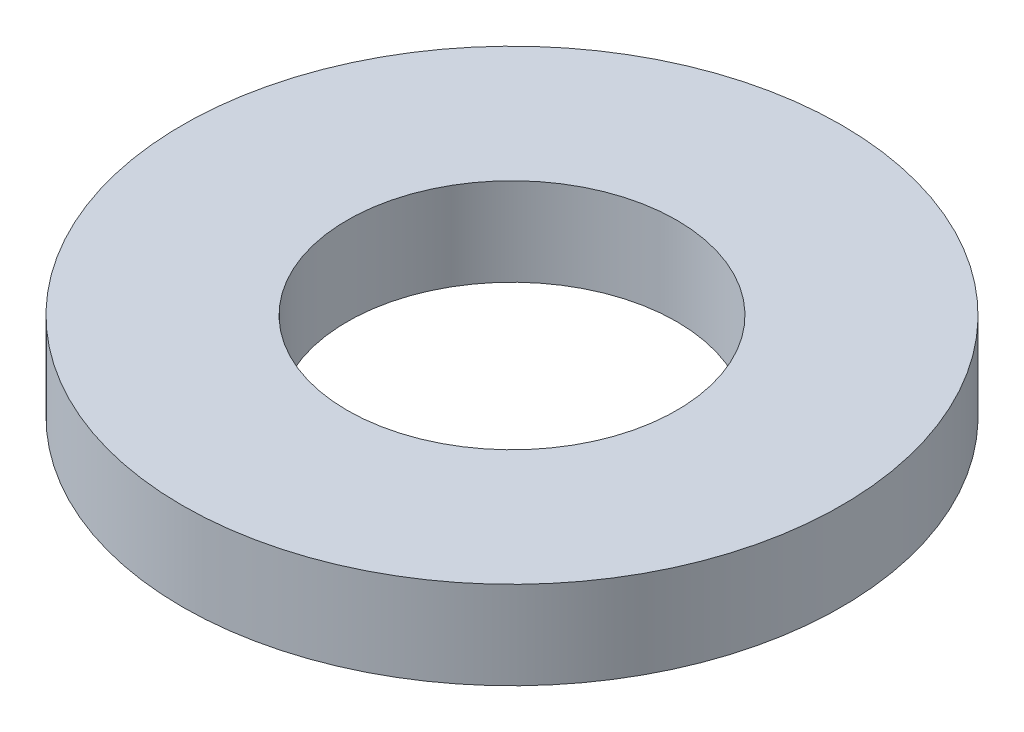
SolidWorks part; units mm, degrees
ref_plane "前视基准面" through (0, 0, 0) normal (0, 0, 1) x (1, 0, 0)
ref_plane "上视基准面" through (0, 0, 0) normal (0, 1, 0) x (1, 0, 0)
ref_plane "右视基准面" through (0, 0, 0) normal (1, 0, 0) x (0, 0, -1)
sketch "草图1" plane through (0, 0, 0) normal (0, 1, 0) x (1, 0, 0)
  circle A0 centre (0, 0) radius 1.5
  circle A1 centre (0, 0) radius 3
  dimension "D1" = 3
  dimension "D2" = 6
extrude "凸台-拉伸1" add sketch "草图1" along normal mid plane 0.8
